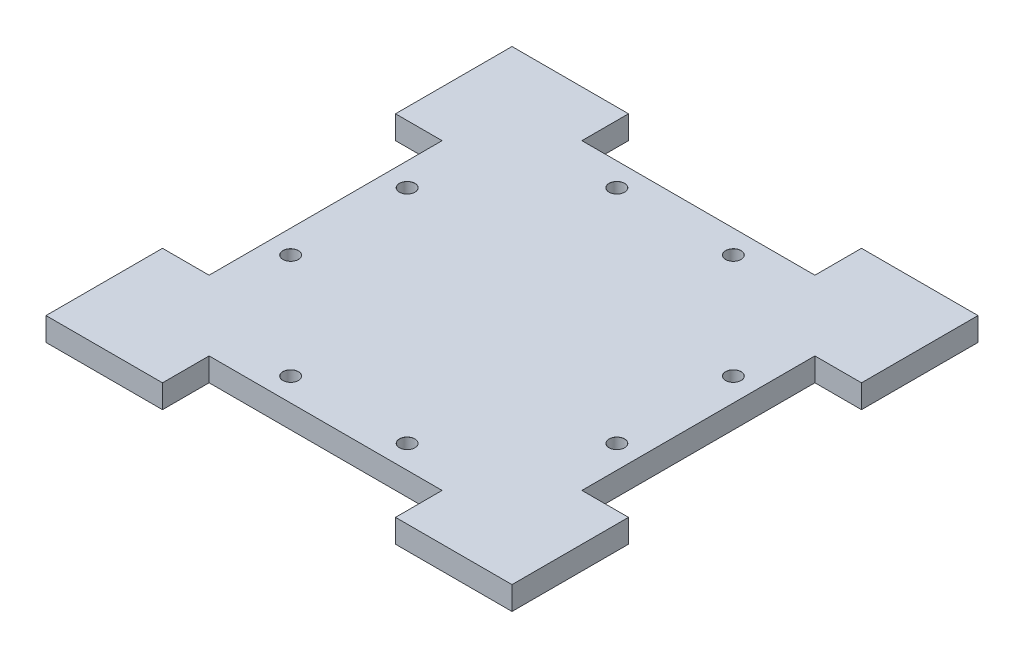
SolidWorks part; units mm, degrees
ref_plane "Front Plane" through (0, 0, 0) normal (0, 0, 1) x (1, 0, 0)
ref_plane "Top Plane" through (0, 0, 0) normal (0, 1, 0) x (1, 0, 0)
ref_plane "Right Plane" through (0, 0, 0) normal (1, 0, 0) x (0, 0, -1)
sketch "Sketch1" plane through (0, 0, 0) normal (0, 1, 0) x (1, 0, 0)
  line L0 (-50, 80) -> (50, 80)
  line L1 (50, 80) -> (50, 100)
  line L2 (50, 100) -> (100, 100)
  line L3 (100, 100) -> (100, 50)
  line L4 (100, 50) -> (80, 50)
  line L5 (80, 50) -> (80, -50)
  line L6 (80, -50) -> (100, -50)
  line L7 (100, -50) -> (100, -100)
  line L8 (100, -100) -> (50, -100)
  line L9 (50, -100) -> (50, -80)
  line L10 (50, -80) -> (-50, -80)
  line L11 (-50, -80) -> (-50, -100)
  line L12 (-50, -100) -> (-100, -100)
  line L13 (-100, -100) -> (-100, -50)
  line L14 (-100, -50) -> (-80, -50)
  line L15 (-80, -50) -> (-80, 50)
  line L16 (-80, 50) -> (-100, 50)
  line L17 (-100, 50) -> (-100, 100)
  line L18 (-100, 100) -> (-50, 100)
  line L19 (-50, 100) -> (-50, 80)
  point P29 (-80, 0)
  point P31 (80, 0)
  point P32 (0, 80)
  point P33 (0, -80)
  dimension "D1" = 20
  dimension "D2" = 200
  dimension "D3" = 200
  dimension "D4" = 100
extrude "Boss-Extrude1" add sketch "Sketch1" along normal blind 10
hole_wizard "M6 Clearance Hole1" positions "Sketch2" profile "Sketch3" hole size "M6" standard "ANSI Metric" end condition through all
sketch "Sketch2" plane through (0, 10, 0) normal (0, 1, 0) x (1, 0, 0)
  line L0 (-70, 25) -> (-70, -25) construction
  line L2 (-25, -70) -> (25, -70) construction
  line L4 (-25, 70) -> (25, 70) construction
  line L6 (70, 25) -> (70, -25) construction
  line L7 (-80, 50) -> (-80, -50) construction
  line L8 (50, 80) -> (-50, 80) construction
  line L9 (80, -50) -> (80, 50) construction
  line L10 (-50, -80) -> (50, -80) construction
  point P0 (-70, -25)
  point P2 (-70, 25)
  point P4 (-25, 70)
  point P6 (25, 70)
  point P8 (70, 25)
  point P10 (70, -25)
  point P12 (-25, -70)
  point P14 (25, -70)
  point P32 (0, 70)
  point P34 (0, -70)
  point P35 (-70, 0)
  point P36 (70, 0)
  dimension "D1" = 50
  dimension "D2" = 10
  dimension "D3" = 10
  dimension "D4" = 10
  dimension "D5" = 10
sketch "Sketch3" plane through (-70, 10, 25) normal (1, 0, 0) x (0, 0, 1)
  line L0 (0, 0) -> (0, 10)
  line L1 (0, 10) -> (3.3, 10)
  line L2 (3.3, 10) -> (3.3, 0.021)
  line L3 (3.3, 0.021) -> (3.325, 0)
  line L5 (3.325, 0) -> (0, 0)
  line L6 (-3.3, 0.021) -> (-3.325, 0) construction
  line L11 (0, -6.35) -> (0, 107.95) construction
  dimension "Thru Hole Dia." = 6.6
  dimension "Thru Hole Depth" = 10
  dimension "Near C'Sink Dia." = 6.65
  dimension "Near C'Sink Angle" = 100
